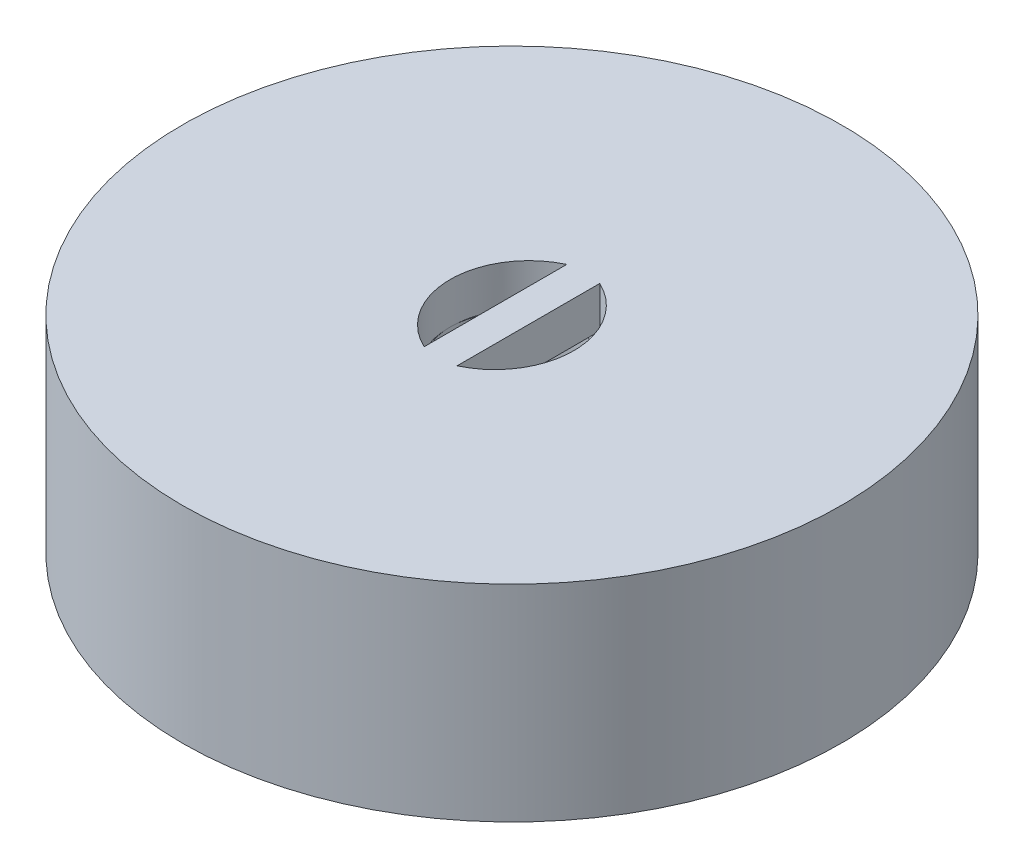
SolidWorks part; units mm, degrees
ref_plane "Front Plane" through (0, 0, 0) normal (0, 0, 1) x (1, 0, 0)
ref_plane "Top Plane" through (0, 0, 0) normal (0, 1, 0) x (1, 0, 0)
ref_plane "Right Plane" through (0, 0, 0) normal (1, 0, 0) x (0, 0, -1)
sketch "Sketch1" plane through (0, 0, 0) normal (0, 1, 0) x (1, 0, 0)
  circle A0 centre (0, 0) radius 1
  dimension "D1" = 2
extrude "Boss-Extrude1" add sketch "Sketch1" along normal blind 0.625
sketch "Sketch2" plane through (0, 0.625, 0) normal (0, 1, 0) x (1, 0, 0)
  line L0 (-0.05, 0.2165) -> (-0.05, -0.2165)
  line L1 (0.05, 0.2165) -> (0.05, -0.2165)
  arc A0 (-0.05, 0.2165) -> (-0.05, -0.2165) centre (0.0516, 0) ccw
  arc A1 (0.05, 0.2165) -> (0.05, -0.2165) centre (-0.0516, 0) cw
  point P6 (-0.1875, 0)
  point P7 (0.1875, 0)
  dimension "D1" = 0.1
  dimension "D2" = 0.375
extrude "Cut-Extrude2" cut sketch "Sketch2" against normal blind 0.125
sketch "Sketch3" plane through (0, 0, 0) normal (0, -1, 0) x (1, 0, 0)
  circle A0 centre (0, 0) radius 0.375
  dimension "D1" = 0.75
extrude "Boss-Extrude2" add sketch "Sketch3" along normal blind 0.375
sketch "Sketch5" plane through (0, -0.375, 0) normal (0, -1, 0) x (1, 0, 0)
  circle A0 centre (0, 0) radius 0.1875
  dimension "D1" = 0.375
extrude "Cut-Extrude3" cut sketch "Sketch5" against normal blind 0.875
fillet "Fillet1" radius 0.1 1 edges at (0, 0, -0.375)
